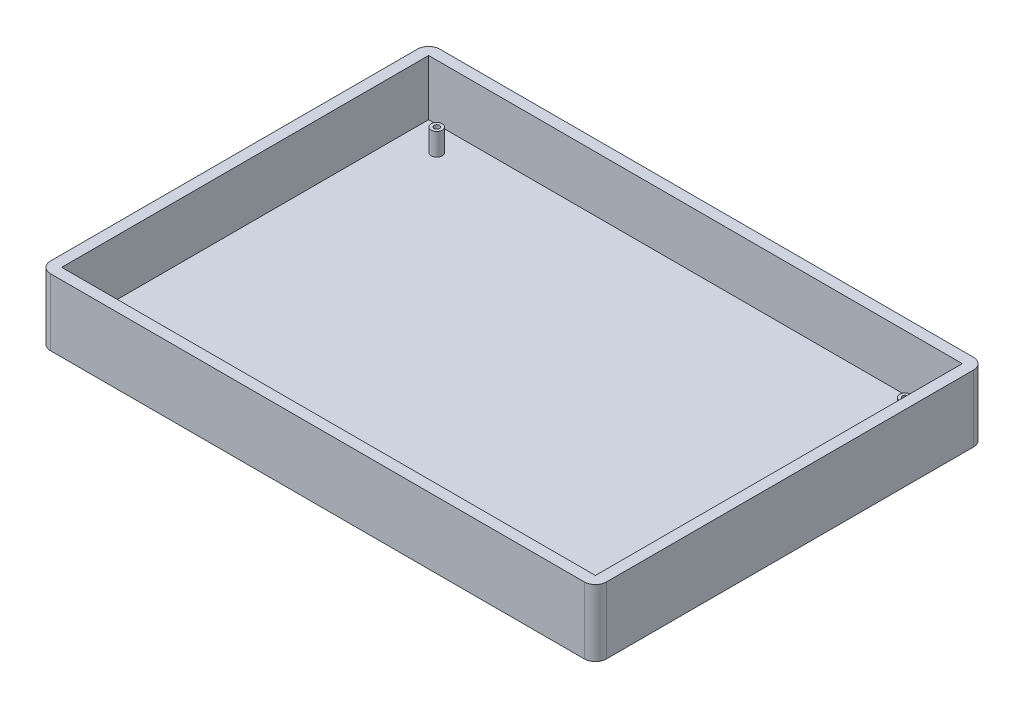
SolidWorks part; units mm, degrees
ref_plane "Plan de face" through (0, 0, 0) normal (0, 0, 1) x (1, 0, 0)
ref_plane "Plan de dessus" through (0, 0, 0) normal (0, 1, 0) x (1, 0, 0)
ref_plane "Plan de droite" through (0, 0, 0) normal (1, 0, 0) x (0, 0, -1)
sketch "Sketch1" plane through (0, 0, 0) normal (0, 1, 0) x (1, 0, 0)
  line L1 (-125, -87.5) -> (125, -87.5)
  line L2 (-125, -87.5) -> (-125, 87.5)
  line L3 (-125, 87.5) -> (125, 87.5)
  line L4 (125, -87.5) -> (125, 87.5)
  line L5 (-125, -87.5) -> (125, 87.5) construction
  line L6 (-125, 87.5) -> (125, -87.5) construction
  point P0 (0, 0)
  dimension "D1" = 250
  dimension "D2" = 175
extrude "Boss-Extrude1" add sketch "Sketch1" along normal blind 30
fillet "Fillet1" radius 5 4 edges at (125, 15, 87.5) (-125, 15, 87.5) (125, 15, -87.5) (-125, 15, -87.5)
sketch "Sketch3" plane through (0, 30, 0) normal (0, 1, 0) x (1, 0, 0)
  line L8 (-120, -82.5) -> (120, -82.5)
  line L9 (120, -82.5) -> (120, 82.5)
  line L10 (120, 82.5) -> (-120, 82.5)
  line L11 (-120, 82.5) -> (-120, -82.5)
  line L12 (-120, -82.5) -> (120, -82.5)
  line L13 (120, -82.5) -> (120, 82.5)
  line L14 (120, 82.5) -> (-120, 82.5)
  line L15 (-120, 82.5) -> (-120, -82.5)
  dimension "D1" = 5
extrude "Cut-Extrude1" cut sketch "Sketch3" against normal blind 25
sketch "Sketch4" plane through (0, 5, 0) normal (0, 1, 0) x (1, 0, 0)
  line L1 (-105.355, -71.49) -> (105.355, -71.49) construction
  line L2 (-105.355, -71.49) -> (-105.355, 71.49) construction
  line L3 (-105.355, 71.49) -> (105.355, 71.49) construction
  line L4 (105.355, -71.49) -> (105.355, 71.49) construction
  line L5 (-105.355, -71.49) -> (105.355, 71.49) construction
  line L6 (-105.355, 71.49) -> (105.355, -71.49) construction
  circle A0 centre (-105.355, 71.49) radius 2.5
  circle A1 centre (105.355, 71.49) radius 2.5
  circle A2 centre (105.355, -71.49) radius 2.5
  circle A3 centre (-105.355, -71.49) radius 2.5
  circle A4 centre (-105.355, 71.49) radius 1.25
  circle A5 centre (105.355, 71.49) radius 1.25
  circle A6 centre (105.355, -71.49) radius 1.25
  circle A7 centre (-105.355, -71.49) radius 1.25
  point P0 (0, 0)
  dimension "D1" = 2.5
  dimension "D2" = 5
  dimension "D3" = 142.98
  dimension "D4" = 210.71
extrude "Boss-Extrude2" add sketch "Sketch4" along normal blind 10
